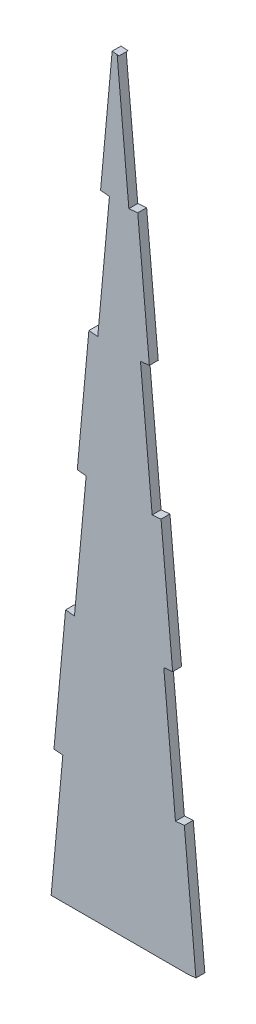
SolidWorks part; units mm, degrees
ref_plane "Front Plane" through (0, 0, 0) normal (0, 0, 1) x (1, 0, 0)
ref_plane "Top Plane" through (0, 0, 0) normal (0, 1, 0) x (1, 0, 0)
ref_plane "Right Plane" through (0, 0, 0) normal (1, 0, 0) x (0, 0, -1)
sketch "Sketch1" plane through (0, 0, 0) normal (0, 0, 1) x (1, 0, 0)
  line L0 (25.1304, 555.2295) -> (29.0382, 597.7575)
  line L1 (29.0382, 597.7575) -> (-103.4039, 609.9272)
  line L2 (-103.4039, 609.9272) -> (-107.3391, 567.1005)
  line L3 (-107.3391, 567.1005) -> (-104.3517, 566.8259)
  line L4 (-104.3517, 566.8259) -> (-108.2595, 524.298)
  line L5 (-108.2595, 524.298) -> (-111.2469, 524.5725)
  line L6 (-111.2469, 524.5725) -> (-115.1821, 481.7457)
  line L7 (-115.1821, 481.7457) -> (-112.1947, 481.4712)
  line L8 (-112.1947, 481.4712) -> (-116.1025, 438.9433)
  line L9 (-116.1025, 438.9433) -> (-119.0899, 439.2178)
  line L10 (-119.0899, 439.2178) -> (-123.0251, 396.391)
  line L11 (-123.0251, 396.391) -> (-120.0377, 396.1165)
  line L12 (-120.0377, 396.1165) -> (-123.9455, 353.5885)
  line L13 (-123.9455, 353.5885) -> (-126.9329, 353.8631)
  line L14 (-126.9329, 353.8631) -> (-130.8681, 311.0363)
  line L15 (-130.8681, 311.0363) -> (-127.8807, 310.7618)
  line L16 (-127.8807, 310.7618) -> (-131.7885, 268.2338)
  line L17 (-131.7885, 268.2338) -> (-134.7759, 268.5083)
  line L18 (-134.7759, 268.5083) -> (-138.7111, 225.6816)
  line L19 (-138.7111, 225.6816) -> (-135.7237, 225.4071)
  line L20 (-135.7237, 225.4071) -> (-139.6315, 182.8791)
  line L21 (-139.6315, 182.8791) -> (-142.6189, 183.1536)
  line L22 (-142.6189, 183.1536) -> (-146.5541, 140.3269)
  line L23 (-146.5541, 140.3269) -> (-143.5667, 140.0524)
  line L24 (-143.5667, 140.0524) -> (-147.4745, 97.5244)
  line L25 (-147.4745, 97.5244) -> (-150.4619, 97.7989)
  line L26 (-150.4619, 97.7989) -> (-154.3971, 54.9722)
  line L27 (-154.3971, 54.9722) -> (-151.4097, 54.6977)
  line L28 (-151.4097, 54.6977) -> (-155.3175, 12.1697)
  line L29 (-155.3175, 12.1697) -> (-22.8754, 0)
  line L30 (-22.8754, 0) -> (-18.9402, 42.8267)
  line L31 (-18.9402, 42.8267) -> (-21.9276, 43.1012)
  line L32 (-21.9276, 43.1012) -> (-18.0198, 85.6292)
  line L33 (-18.0198, 85.6292) -> (-15.0324, 85.3547)
  line L34 (-15.0324, 85.3547) -> (-11.0972, 128.1814)
  line L35 (-11.0972, 128.1814) -> (-14.0846, 128.4559)
  line L36 (-14.0846, 128.4559) -> (-10.1768, 170.9839)
  line L37 (-10.1768, 170.9839) -> (-7.1894, 170.7094)
  line L38 (-7.1894, 170.7094) -> (-3.2542, 213.5361)
  line L39 (-3.2542, 213.5361) -> (-6.2416, 213.8106)
  line L40 (-6.2416, 213.8106) -> (-2.3338, 256.3386)
  line L41 (-2.3338, 256.3386) -> (0.6536, 256.0641)
  line L42 (0.6536, 256.0641) -> (4.5888, 298.8908)
  line L43 (4.5888, 298.8908) -> (1.6014, 299.1654)
  line L44 (1.6014, 299.1654) -> (5.5092, 341.6933)
  line L45 (5.5092, 341.6933) -> (8.4966, 341.4188)
  line L46 (8.4966, 341.4188) -> (12.4318, 384.2456)
  line L47 (12.4318, 384.2456) -> (9.4444, 384.5201)
  line L48 (9.4444, 384.5201) -> (13.3522, 427.048)
  line L49 (13.3522, 427.048) -> (16.3396, 426.7735)
  line L50 (16.3396, 426.7735) -> (20.2748, 469.6003)
  line L51 (20.2748, 469.6003) -> (17.2874, 469.8748)
  line L52 (17.2874, 469.8748) -> (21.1952, 512.4028)
  line L53 (21.1952, 512.4028) -> (24.1826, 512.1282)
  line L54 (24.1826, 512.1282) -> (28.1178, 554.955)
  line L55 (28.1178, 554.955) -> (25.1304, 555.2295)
  line L56 (22.8754, 0) -> (-22.8754, 0)
  line L57 (0, 0) -> (0, 248.9512) construction
  line L58 (-109.7532, 524.4352) -> (-109.7806, 524.1365) construction
  line L59 (-109.7806, 524.1365) -> (-113.6884, 481.6085) construction
  line L60 (-37.1829, 603.8423) -> (-92.0838, 6.3594) construction
  line L61 (104.3243, 567.1247) -> (100.4165, 609.6527)
  line L62 (100.4165, 609.6527) -> (-32.0256, 597.483)
  line L63 (-32.0256, 597.483) -> (-28.0903, 554.6562)
  line L64 (-28.0903, 554.6562) -> (-25.1029, 554.9307)
  line L65 (-25.1029, 554.9307) -> (-21.1952, 512.4028)
  line L66 (-21.1952, 512.4028) -> (-24.1826, 512.1282)
  line L67 (-24.1826, 512.1282) -> (-20.2473, 469.3015)
  line L68 (-20.2473, 469.3015) -> (-17.2599, 469.576)
  line L69 (-17.2599, 469.576) -> (-13.3522, 427.048)
  line L70 (-13.3522, 427.048) -> (-16.3396, 426.7735)
  line L71 (-16.3396, 426.7735) -> (-12.4044, 383.9468)
  line L72 (-12.4044, 383.9468) -> (-9.4169, 384.2213)
  line L73 (-9.4169, 384.2213) -> (-5.5092, 341.6933)
  line L74 (-5.5092, 341.6933) -> (-8.4966, 341.4188)
  line L75 (-8.4966, 341.4188) -> (-4.5614, 298.5921)
  line L76 (-4.5614, 298.5921) -> (-1.5739, 298.8666)
  line L77 (-1.5739, 298.8666) -> (2.3338, 256.3386)
  line L78 (2.3338, 256.3386) -> (-0.6536, 256.0641)
  line L79 (-0.6536, 256.0641) -> (3.2816, 213.2374)
  line L80 (3.2816, 213.2374) -> (6.2691, 213.5119)
  line L81 (6.2691, 213.5119) -> (10.1768, 170.9839)
  line L82 (10.1768, 170.9839) -> (7.1894, 170.7094)
  line L83 (7.1894, 170.7094) -> (11.1246, 127.8827)
  line L84 (11.1246, 127.8827) -> (14.1121, 128.1572)
  line L85 (14.1121, 128.1572) -> (18.0198, 85.6292)
  line L86 (18.0198, 85.6292) -> (15.0324, 85.3547)
  line L87 (15.0324, 85.3547) -> (18.9676, 42.528)
  line L88 (18.9676, 42.528) -> (21.955, 42.8025)
  line L89 (21.955, 42.8025) -> (25.8628, 0.2745)
  line L90 (25.8628, 0.2745) -> (158.3049, 12.4442)
  line L91 (158.3049, 12.4442) -> (154.3697, 55.2709)
  line L92 (154.3697, 55.2709) -> (151.3822, 54.9964)
  line L93 (151.3822, 54.9964) -> (147.4745, 97.5244)
  line L94 (147.4745, 97.5244) -> (150.4619, 97.7989)
  line L95 (150.4619, 97.7989) -> (146.5267, 140.6257)
  line L96 (146.5267, 140.6257) -> (143.5392, 140.3511)
  line L97 (143.5392, 140.3511) -> (139.6315, 182.8791)
  line L98 (139.6315, 182.8791) -> (142.6189, 183.1536)
  line L99 (142.6189, 183.1536) -> (138.6837, 225.9804)
  line L100 (138.6837, 225.9804) -> (135.6962, 225.7059)
  line L101 (135.6962, 225.7059) -> (131.7885, 268.2338)
  line L102 (131.7885, 268.2338) -> (134.7759, 268.5083)
  line L103 (134.7759, 268.5083) -> (130.8407, 311.3351)
  line L104 (130.8407, 311.3351) -> (127.8532, 311.0606)
  line L105 (127.8532, 311.0606) -> (123.9455, 353.5885)
  line L106 (123.9455, 353.5885) -> (126.9329, 353.8631)
  line L107 (126.9329, 353.8631) -> (122.9977, 396.6898)
  line L108 (122.9977, 396.6898) -> (120.0103, 396.4153)
  line L109 (120.0103, 396.4153) -> (116.1025, 438.9433)
  line L110 (116.1025, 438.9433) -> (119.0899, 439.2178)
  line L111 (119.0899, 439.2178) -> (115.1547, 482.0445)
  line L168 (115.1547, 482.0445) -> (112.1673, 481.77)
  line L169 (112.1673, 481.77) -> (108.2595, 524.298)
  line L170 (108.2595, 524.298) -> (111.2469, 524.5725)
  line L171 (111.2469, 524.5725) -> (107.3117, 567.3992)
  line L172 (107.3117, 567.3992) -> (104.3243, 567.1247)
  line L173 (-22.6889, 512.2655) -> (-22.6614, 511.9668) construction
  line L174 (-22.6614, 511.9668) -> (-18.7536, 469.4388) construction
  line L175 (34.1955, 603.5678) -> (89.0964, 6.0849) construction
  line L176 (22.8754, 0) -> (25.8628, 0.2745)
  dimension "D1" = 3
  dimension "D2" = 10.5
  dimension "D3" = 600
  dimension "D4" = 250
  dimension "D5" = 130
  dimension "D6" = 0.3
extrude "Boss-Extrude1" add sketch "Sketch1" along normal blind 3 contours L56 L176 L89 L88 L87 L86 L85 L84 L83 L82 L81 L80 L79 L78 L41 L40 L39 L38 L37 L36 L35 L34 L33 L32 L31 L30
